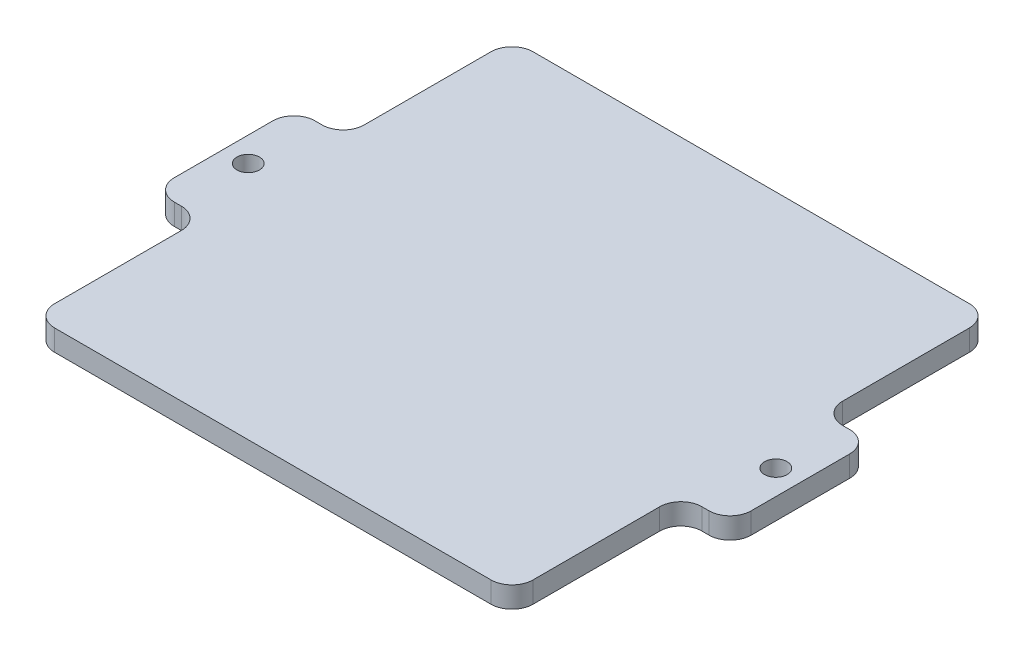
SolidWorks part; units mm, degrees
ref_plane "Front Plane" through (0, 0, 0) normal (0, 0, 1) x (1, 0, 0)
ref_plane "Top Plane" through (0, 0, 0) normal (0, 1, 0) x (1, 0, 0)
ref_plane "Right Plane" through (0, 0, 0) normal (1, 0, 0) x (0, 0, -1)
sketch "Sketch1" plane through (0, 0, 0) normal (0, 1, 0) x (1, 0, 0)
  line L1 (-34, 34) -> (34, 34)
  line L2 (-34, 34) -> (-34, -34)
  line L3 (-34, -34) -> (34, -34)
  line L4 (34, 34) -> (34, -34)
  line L5 (-34, 34) -> (34, -34) construction
  line L6 (-34, -34) -> (34, 34) construction
  point P0 (0, 0)
  dimension "D1" = 68
  dimension "D2" = 68
extrude "Boss-Extrude1" add sketch "Sketch1" along normal blind 3
sketch "Sketch2" plane through (0, 3, 0) normal (0, 1, 0) x (1, 0, 0)
  line L0 (-37.5, 0) -> (0, 0) construction
  line L1 (41, 10) -> (34, 10)
  line L2 (41, 10) -> (41, -10)
  line L3 (41, -10) -> (34, -10)
  line L4 (34, 10) -> (34, -10)
  line L5 (41, 10) -> (34, -10) construction
  line L6 (41, -10) -> (34, 10) construction
  line L7 (-34, 10) -> (-41, 10)
  line L8 (-34, 10) -> (-34, -10)
  line L9 (-34, -10) -> (-41, -10)
  line L10 (-41, 10) -> (-41, -10)
  line L11 (-34, 10) -> (-41, -10) construction
  line L12 (-34, -10) -> (-41, 10) construction
  line L13 (0, 0) -> (37.5, 0) construction
  line L14 (-34, 34) -> (-34, -34) construction
  line L15 (34, -34) -> (34, 34) construction
  circle A0 centre (-37.5, 0) radius 1.6
  circle A1 centre (37.5, 0) radius 1.6
  point P0 (37.5, 0)
  point P5 (-37.5, 0)
  dimension "D1" = 3.2
  dimension "D2" = 75
  dimension "D3" = 20
extrude "Boss-Extrude2" add sketch "Sketch2" against normal up to surface (3 mm away) up to face at (0, 0, 0)
fillet "Fillet1" radius 3 12 edges at (41, 1.5, 10) (41, 1.5, -10) (-41, 1.5, -10) (-41, 1.5, 10) (-34, 1.5, 34) (34, 1.5, 34) (34, 1.5, -34) (-34, 1.5, -34)
